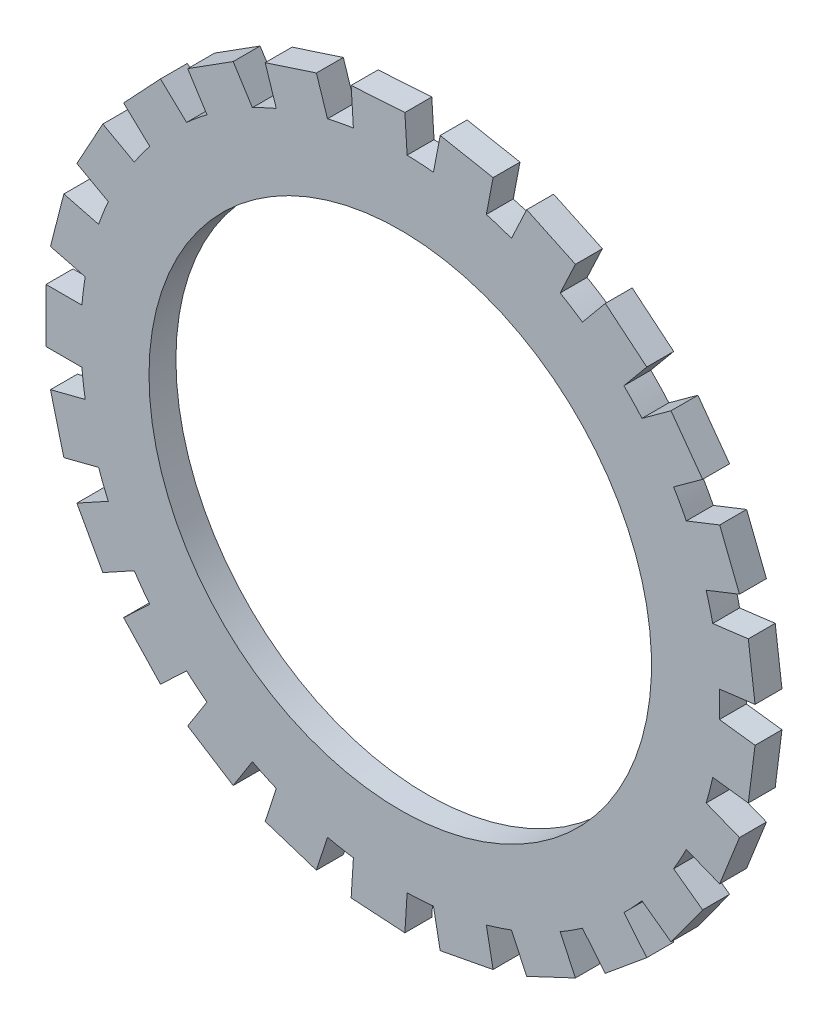
SolidWorks part; units mm, degrees
ref_plane "Front Plane" through (0, 0, 0) normal (0, 0, 1) x (1, 0, 0)
ref_plane "Top Plane" through (0, 0, 0) normal (0, 1, 0) x (1, 0, 0)
ref_plane "Right Plane" through (0, 0, 0) normal (1, 0, 0) x (0, 0, -1)
sketch "Sketch1" plane through (0, 0, 0) normal (0, 0, 1) x (1, 0, 0)
  circle A0 centre (0, 0) radius 226.06
  circle A1 centre (0, 0) radius 177.8
  dimension "D1" = 452.12
  dimension "D2" = 355.6
extrude "Boss-Extrude1" add sketch "Sketch1" along normal blind 19.05
sketch "Sketch2" plane through (0, 0, 19.05) normal (0, 0, 1) x (1, 0, 0)
  line L0 (0, 0) -> (-483.5191, 0) construction
  line L1 (-250.6559, 19.05) -> (-225.2559, 19.05)
  line L2 (-250.6559, 19.05) -> (-250.6559, -19.05)
  line L3 (-250.6559, -19.05) -> (-225.2559, -19.05)
  line L4 (-247.5186, 43.8841) -> (-222.9166, 37.5674)
  line L5 (-238.0435, 80.7871) -> (-247.5186, 43.8841)
  line L6 (-238.0435, 80.7871) -> (-213.4415, 74.4704)
  line L7 (-228.8288, 104.0608) -> (-206.5707, 91.8242)
  line L8 (-210.474, 137.448) -> (-228.8288, 104.0608)
  line L9 (-210.474, 137.448) -> (-188.2158, 125.2115)
  line L10 (-195.7609, 157.6989) -> (-177.2451, 140.3114)
  line L11 (-169.6797, 185.4726) -> (-195.7609, 157.6989)
  line L12 (-169.6797, 185.4726) -> (-151.1639, 168.0851)
  line L13 (-150.3926, 201.4283) -> (-136.7826, 179.9823)
  line L14 (-118.2237, 221.8433) -> (-150.3926, 201.4283)
  line L15 (-118.2237, 221.8433) -> (-104.6137, 200.3973)
  line L16 (-95.5746, 232.5012) -> (-87.7255, 208.3443)
  line L17 (-59.3393, 244.2747) -> (-95.5746, 232.5012)
  line L18 (-59.3393, 244.2747) -> (-51.4903, 220.1179)
  line L19 (-34.7512, 248.9651) -> (-33.1563, 223.6153)
  line L20 (3.2736, 251.3574) -> (-34.7512, 248.9651)
  line L21 (3.2736, 251.3574) -> (4.8685, 226.0076)
  line L22 (28.2557, 249.7857) -> (23.4962, 224.8356)
  line L23 (65.6808, 242.6465) -> (28.2557, 249.7857)
  line L24 (65.6808, 242.6465) -> (60.9213, 217.6964)
  line L25 (89.4871, 234.9113) -> (78.6723, 211.9287)
  line L26 (123.961, 218.6891) -> (89.4871, 234.9113)
  line L27 (123.961, 218.6891) -> (113.1463, 195.7065)
  line L28 (145.0958, 205.2766) -> (128.9052, 185.7056)
  line L29 (174.4524, 180.9908) -> (145.0958, 205.2766)
  line L30 (174.4524, 180.9908) -> (158.2618, 161.4197)
  line L31 (191.5876, 162.7436) -> (171.0385, 147.8139)
  line L32 (213.9822, 131.9201) -> (191.5876, 162.7436)
  line L33 (213.9822, 131.9201) -> (193.4332, 116.9903)
  line L34 (226.0412, 109.9848) -> (202.4249, 100.6345)
  line L35 (240.0667, 74.5603) -> (226.0412, 109.9848)
  line L36 (240.0667, 74.5603) -> (216.4504, 65.21)
  line L37 (246.2918, 50.3153) -> (221.0921, 47.1318)
  line L38 (251.067, 12.5157) -> (246.2918, 50.3153)
  line L39 (251.067, 12.5157) -> (225.8673, 9.3323)
  line L40 (251.067, -12.5157) -> (225.8673, -9.3323)
  line L41 (246.2918, -50.3153) -> (251.067, -12.5157)
  line L42 (246.2918, -50.3153) -> (221.0921, -47.1318)
  line L43 (240.0667, -74.5603) -> (216.4504, -65.21)
  line L44 (226.0412, -109.9848) -> (240.0667, -74.5603)
  line L45 (226.0412, -109.9848) -> (202.4249, -100.6345)
  line L46 (213.9822, -131.9201) -> (193.4332, -116.9903)
  line L47 (191.5876, -162.7436) -> (213.9822, -131.9201)
  line L48 (191.5876, -162.7436) -> (171.0385, -147.8139)
  line L49 (174.4524, -180.9908) -> (158.2618, -161.4197)
  line L50 (145.0958, -205.2766) -> (174.4524, -180.9908)
  line L51 (145.0958, -205.2766) -> (128.9052, -185.7056)
  line L52 (123.961, -218.6891) -> (113.1463, -195.7065)
  line L53 (89.4871, -234.9113) -> (123.961, -218.6891)
  line L54 (89.4871, -234.9113) -> (78.6723, -211.9287)
  line L55 (65.6808, -242.6465) -> (60.9213, -217.6964)
  line L56 (28.2557, -249.7857) -> (65.6808, -242.6465)
  line L57 (28.2557, -249.7857) -> (23.4962, -224.8356)
  line L58 (3.2736, -251.3574) -> (4.8685, -226.0076)
  line L59 (-34.7512, -248.9651) -> (3.2736, -251.3574)
  line L60 (-34.7512, -248.9651) -> (-33.1563, -223.6153)
  line L61 (-59.3393, -244.2747) -> (-51.4903, -220.1179)
  line L62 (-95.5746, -232.5012) -> (-59.3393, -244.2747)
  line L63 (-95.5746, -232.5012) -> (-87.7255, -208.3443)
  line L64 (-118.2237, -221.8433) -> (-104.6137, -200.3973)
  line L65 (-150.3926, -201.4283) -> (-118.2237, -221.8433)
  line L66 (-150.3926, -201.4283) -> (-136.7826, -179.9823)
  line L67 (-169.6797, -185.4726) -> (-151.1639, -168.0851)
  line L68 (-195.7609, -157.6989) -> (-169.6797, -185.4726)
  line L69 (-195.7609, -157.6989) -> (-177.2451, -140.3114)
  line L70 (-210.474, -137.448) -> (-188.2158, -125.2115)
  line L71 (-228.8288, -104.0608) -> (-210.474, -137.448)
  line L72 (-228.8288, -104.0608) -> (-206.5707, -91.8242)
  line L73 (-238.0435, -80.7871) -> (-213.4415, -74.4704)
  line L74 (-247.5186, -43.8841) -> (-238.0435, -80.7871)
  line L75 (-247.5186, -43.8841) -> (-222.9166, -37.5674)
  arc A0 (-225.2559, 19.05) -> (-225.2559, -19.05) centre (0, 0) ccw
  arc A1 (-213.4415, 74.4704) -> (-222.9166, 37.5674) centre (0, 0) ccw
  arc A2 (-188.2158, 125.2115) -> (-206.5707, 91.8242) centre (0, 0) ccw
  arc A3 (-151.1639, 168.0851) -> (-177.2451, 140.3114) centre (0, 0) ccw
  arc A4 (-104.6137, 200.3973) -> (-136.7826, 179.9823) centre (0, 0) ccw
  arc A5 (-51.4903, 220.1179) -> (-87.7255, 208.3443) centre (0, 0) ccw
  arc A6 (4.8685, 226.0076) -> (-33.1563, 223.6153) centre (0, 0) ccw
  arc A7 (60.9213, 217.6964) -> (23.4962, 224.8356) centre (0, 0) ccw
  arc A8 (113.1463, 195.7065) -> (78.6723, 211.9287) centre (0, 0) ccw
  arc A9 (158.2618, 161.4197) -> (128.9052, 185.7056) centre (0, 0) ccw
  arc A10 (193.4332, 116.9903) -> (171.0385, 147.8139) centre (0, 0) ccw
  arc A11 (216.4504, 65.21) -> (202.4249, 100.6345) centre (0, 0) ccw
  arc A12 (225.8673, 9.3323) -> (221.0921, 47.1318) centre (0, 0) ccw
  arc A13 (221.0921, -47.1318) -> (225.8673, -9.3323) centre (0, 0) ccw
  arc A14 (202.4249, -100.6345) -> (216.4504, -65.21) centre (0, 0) ccw
  arc A15 (171.0385, -147.8139) -> (193.4332, -116.9903) centre (0, 0) ccw
  arc A16 (128.9052, -185.7056) -> (158.2618, -161.4197) centre (0, 0) ccw
  arc A17 (78.6723, -211.9287) -> (113.1463, -195.7065) centre (0, 0) ccw
  arc A18 (23.4962, -224.8356) -> (60.9213, -217.6964) centre (0, 0) ccw
  arc A19 (-33.1563, -223.6153) -> (4.8685, -226.0076) centre (0, 0) ccw
  arc A20 (-87.7255, -208.3443) -> (-51.4903, -220.1179) centre (0, 0) ccw
  arc A21 (-136.7826, -179.9823) -> (-104.6137, -200.3973) centre (0, 0) ccw
  arc A22 (-177.2451, -140.3114) -> (-151.1639, -168.0851) centre (0, 0) ccw
  arc A23 (-206.5707, -91.8242) -> (-188.2158, -125.2115) centre (0, 0) ccw
  arc A24 (-222.9166, -37.5674) -> (-213.4415, -74.4704) centre (0, 0) ccw
  dimension "D2" = 452.12
  dimension "D1" = 38.1
  dimension "D3" = 25.4
  dimension "D4" = 25.4
  dimension "D5" = 25
extrude "Boss-Extrude2" add sketch "Sketch2" against normal blind 19.05
